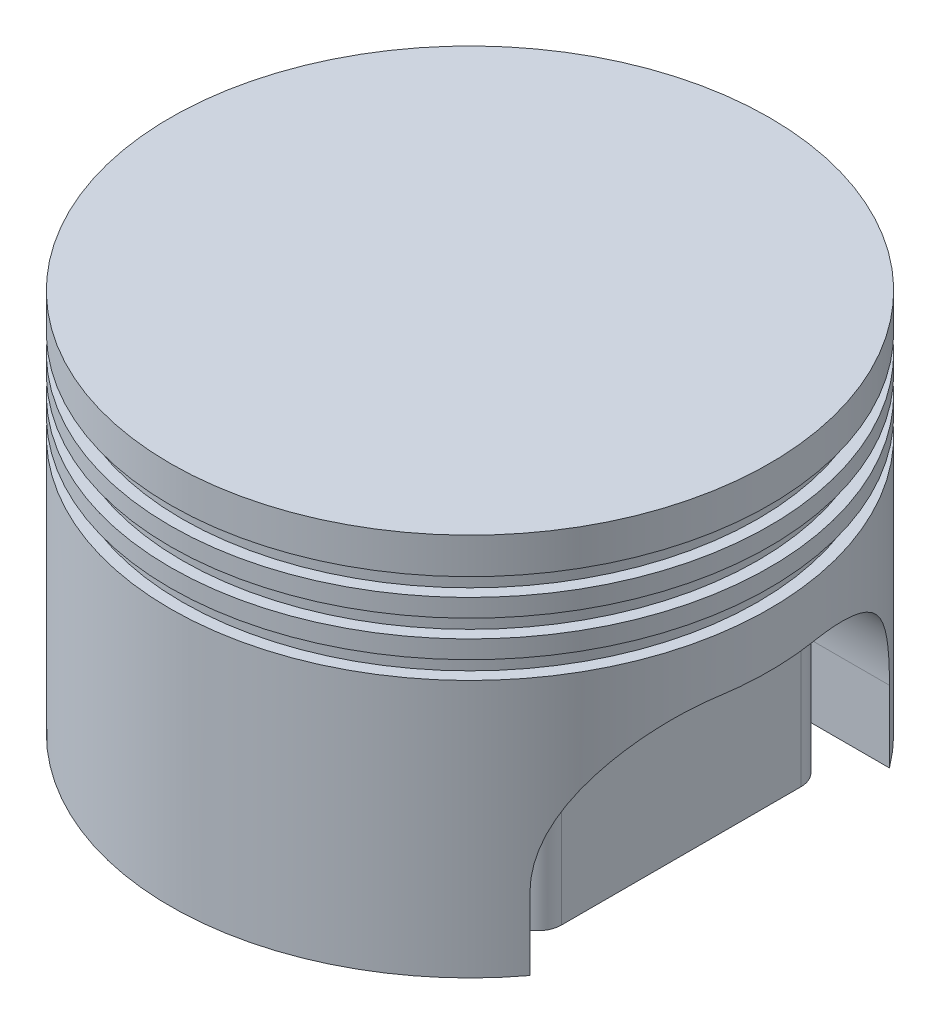
SolidWorks part; units mm, degrees
ref_plane "Front Plane" through (0, 0, 0) normal (0, 0, 1) x (1, 0, 0)
ref_plane "Top Plane" through (0, 0, 0) normal (0, 1, 0) x (1, 0, 0)
ref_plane "Right Plane" through (0, 0, 0) normal (1, 0, 0) x (0, 0, -1)
sketch "Sketch2" plane through (0, 0, 0) normal (0, 0, 1) x (1, 0, 0)
  line L0 (0, 21.9341) -> (0, -106.9441) construction
  line L1 (0, 0) -> (-63.5, 0)
  line L2 (-63.5, 0) -> (-63.5, -81.28)
  line L3 (-63.5, -81.28) -> (-37.7, -81.28)
  line L4 (-37.7, -81.28) -> (-37.7, -38.1)
  line L5 (-37.7, -38.1) -> (0, -38.1)
  line L6 (0, -38.1) -> (0, 0)
revolve "Revolve4" add sketch "Sketch2" angle 360 about L6
ref_plane "Plane2" through (-63.5, 0, 0) normal (-1, 0, 0) x (0, 0, 1)
sketch "Sketch3" plane through (-63.5, 0, 0) normal (-1, 0, 0) x (0, 0, 1)
  line L0 (0, 0) -> (0, -81.28) construction
  line L1 (-63.5, -81.28) -> (63.5, -81.28) construction
  line L2 (10.1, -38.1) -> (-10.1, -38.1)
  line L3 (-38.1, -66.1) -> (-38.1, -81.28)
  line L4 (38.1, -66.1) -> (38.1, -81.28)
  line L5 (-38.1, -81.28) -> (0, -81.28)
  line L6 (0, -81.28) -> (38.1, -81.28)
  arc A0 (-10.1, -38.1) -> (-38.1, -66.1) centre (-10.1, -66.1) ccw
  arc A1 (10.1, -38.1) -> (38.1, -66.1) centre (10.1, -66.1) cw
  point P10 (-38.1, -38.1)
  point P13 (0, -38.1)
  dimension "D3" = 28
  dimension "D1" = 43.18
  dimension "D2" = 38.1
extrude "Cut-Extrude2" cut sketch "Sketch3" against normal blind 158
sketch "Sketch4" plane through (-63.5, 0, 0) normal (-1, 0, 0) x (0, 0, 1)
  line L0 (0, 0) -> (0, -85.4582) construction
  line L13 (0, 0) -> (0, -89.475) construction
ref_plane "Plane3" through (0, 0, 0) normal (1, 0, 0) x (0, 0, -1)
sketch "Sketch5" plane through (0, 0, 0) normal (1, 0, 0) x (0, 0, -1)
  line L0 (0, 0) -> (0, -93.8241) construction
  line L1 (75.1789, -11.43) -> (61, -11.43)
  line L6 (61, -7.62) -> (75.1789, -7.62)
  line L7 (75.1789, -7.62) -> (75.1789, -11.43)
  line L8 (61, -11.43) -> (61, -7.62)
  line L9 (63.5, 0) -> (-63.5, 0) construction
  line L10 (63.5, -81.28) -> (63.5, 0) construction
  line L11 (61, -15.24) -> (70.3598, -15.24)
  line L12 (61, -15.24) -> (61, -19.05)
  line L13 (61, -19.05) -> (70.3598, -19.05)
  line L14 (70.3598, -15.24) -> (70.3598, -19.05)
  line L15 (61, -26.67) -> (70.3598, -26.67)
  line L16 (61, -26.67) -> (61, -22.86)
  line L17 (61, -22.86) -> (70.3598, -22.86)
  line L18 (70.3598, -26.67) -> (70.3598, -22.86)
  point P19 (61, -17.145)
  dimension "D1" = 3.81
  dimension "D2" = 7.62
  dimension "D3" = 3.81
  dimension "D4" = 3.81
  dimension "D5" = 3.81
  dimension "D6" = 3.81
  dimension "D7" = 2.5
  dimension "D8" = 2.5
  dimension "D9" = 2.5
revolve "Cut-Revolve6" cut sketch "Sketch5" angle 360 about L0
ref_plane "Plane5" through (0, -38.1, 0) normal (0, 1, 0) x (1, 0, 0)
sketch "Sketch6" plane through (0, -38.1, 0) normal (0, 1, 0) x (1, 0, 0)
  line L0 (0, 69.9386) -> (0, -70.1168) construction
  line L1 (0, -49.2112) -> (0, 49.2112) construction
  line L3 (15.8796, -25.5088) -> (15.8796, 25.2912)
  line L4 (20.8796, 30.2912) -> (39.8796, 30.2912)
  line L5 (44.8796, 25.2912) -> (44.8796, -25.5088)
  line L6 (20.8796, -20.5088) -> (20.8796, 20.2912)
  line L7 (25.8796, 25.2912) -> (34.8796, 25.2912)
  line L8 (39.8796, 20.2912) -> (39.8796, -20.5088)
  line L13 (25.8796, -25.5088) -> (34.8796, -25.5088)
  line L14 (20.8796, -30.5088) -> (39.8796, -30.5088)
  line L17 (-39.8796, 20.2912) -> (-39.8796, -20.5088)
  line L18 (-25.8796, 25.2912) -> (-34.8796, 25.2912)
  line L19 (-20.8796, -20.5088) -> (-20.8796, 20.2912)
  line L20 (-44.8796, 25.2912) -> (-44.8796, -25.5088)
  line L21 (-20.8796, 30.2912) -> (-39.8796, 30.2912)
  line L22 (-15.8796, -25.5088) -> (-15.8796, 25.2912)
  line L23 (-20.8796, -30.5088) -> (-39.8796, -30.5088)
  line L24 (-25.8796, -25.5088) -> (-34.8796, -25.5088)
  arc A0 (20.8796, 30.2912) -> (15.8796, 25.2912) centre (20.8796, 25.2912) ccw
  arc A1 (39.8796, 20.2912) -> (34.8796, 25.2912) centre (34.8796, 20.2912) ccw
  arc A2 (25.8796, 25.2912) -> (20.8796, 20.2912) centre (25.8796, 20.2912) ccw
  arc A3 (44.8796, 25.2912) -> (39.8796, 30.2912) centre (39.8796, 25.2912) ccw
  arc A4 (25.8796, -25.5088) -> (20.8796, -20.5088) centre (25.8796, -20.5088) cw
  arc A5 (39.8796, -20.5088) -> (34.8796, -25.5088) centre (34.8796, -20.5088) cw
  arc A6 (20.8796, -30.5088) -> (15.8796, -25.5088) centre (20.8796, -25.5088) cw
  arc A7 (39.8796, -30.5088) -> (44.8796, -25.5088) centre (39.8796, -25.5088) ccw
  arc A8 (-44.8796, 25.2912) -> (-39.8796, 30.2912) centre (-39.8796, 25.2912) cw
  arc A9 (-25.8796, 25.2912) -> (-20.8796, 20.2912) centre (-25.8796, 20.2912) cw
  arc A10 (-39.8796, 20.2912) -> (-34.8796, 25.2912) centre (-34.8796, 20.2912) cw
  arc A11 (-20.8796, 30.2912) -> (-15.8796, 25.2912) centre (-20.8796, 25.2912) cw
  arc A12 (-39.8796, -30.5088) -> (-44.8796, -25.5088) centre (-39.8796, -25.5088) cw
  arc A13 (-20.8796, -30.5088) -> (-15.8796, -25.5088) centre (-20.8796, -25.5088) ccw
  arc A14 (-39.8796, -20.5088) -> (-34.8796, -25.5088) centre (-34.8796, -20.5088) ccw
  arc A15 (-25.8796, -25.5088) -> (-20.8796, -20.5088) centre (-25.8796, -20.5088) ccw
  point P5 (0, 0)
  point P6 (0, 0)
  point P17 (15.8796, 30.2912)
  point P24 (44.8796, 30.2912)
  point P29 (39.8796, -0.1088)
  point P30 (20.8796, -0.1088)
  point P36 (44.8796, -0.1088)
  point P40 (15.8796, -0.1088)
  point P59 (-44.8796, 30.2912)
  point P60 (-15.8796, 30.2912)
  point P71 (-15.8796, -0.1088)
  point P72 (-44.8796, -0.1088)
  point P73 (-20.8796, -0.1088)
  point P74 (-39.8796, -0.1088)
  point P75 (0, -0.0891)
  dimension "D7" = 5
  dimension "D8" = 5
  dimension "D9" = 15.8796
  dimension "D1" = 15.88
  dimension "D2" = 29
  dimension "D4" = 5
  dimension "D5" = 5
  dimension "D6" = 15.8796
extrude "Boss-Extrude3" add sketch "Sketch6" against normal blind 43.18
